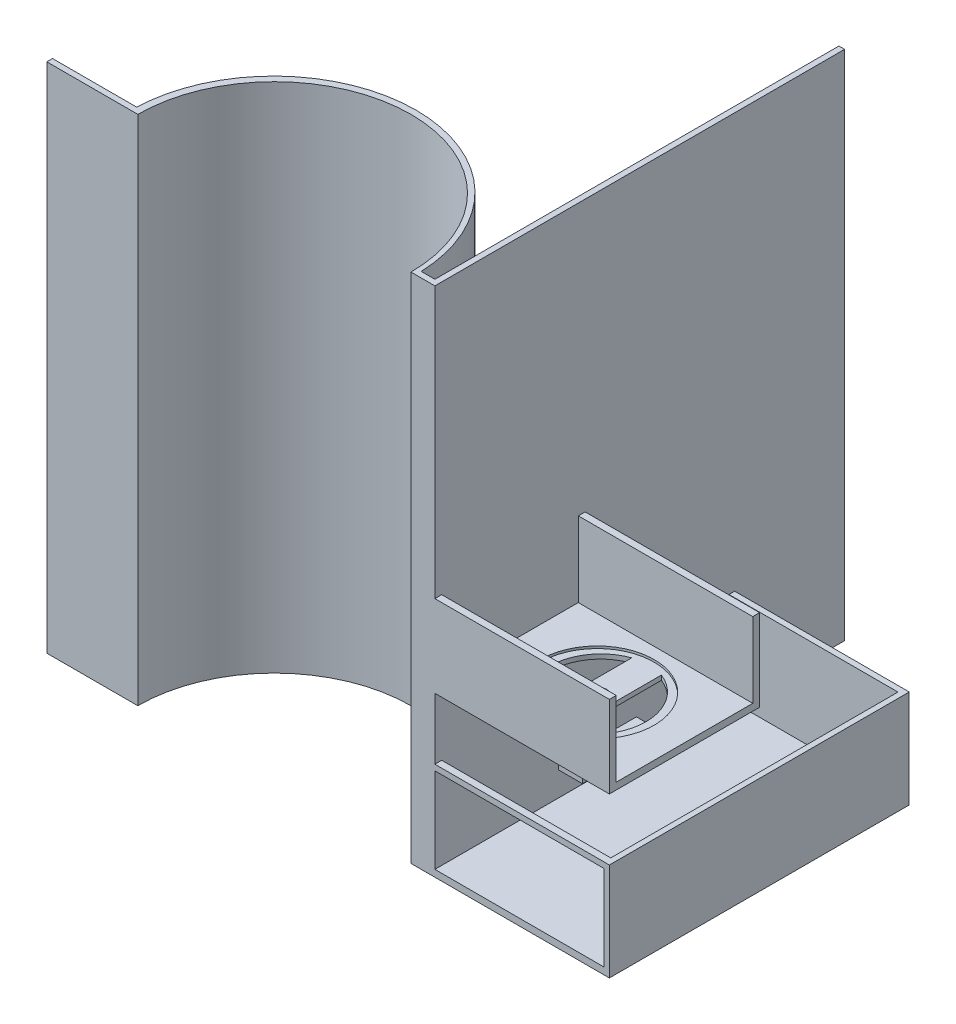
SolidWorks part; units mm, degrees
ref_plane "前视基准面" through (0, 0, 0) normal (0, 0, 1) x (1, 0, 0)
ref_plane "上视基准面" through (0, 0, 0) normal (0, 1, 0) x (1, 0, 0)
ref_plane "右视基准面" through (0, 0, 0) normal (1, 0, 0) x (0, 0, -1)
sketch "草图1" plane through (0, 0, 0) normal (0, 1, 0) x (1, 0, 0)
  line L0 (0, 0) -> (40, 0)
  line L4 (0, 0) -> (0, 2.5)
  line L5 (0, 2.5) -> (37, 2.5)
  line L6 (160, 0) -> (170.5, 0)
  line L10 (170.5, 0) -> (170.5, 180)
  line L11 (170.5, 180) -> (168, 180)
  line L12 (168, 180) -> (168, 2.5)
  line L13 (168, 2.5) -> (162, 2.5)
  arc A0 (40, 0) -> (160, 0) centre (100, 0) cw
  arc A1 (37, 2.5) -> (162, 2.5) centre (99.5, 0.1775) cw
  point P3 (160, 0)
  dimension "120" = 120
extrude "凸台-拉伸1" add sketch "草图1" along normal blind 225
ref_plane "基准面5" through (170.5, 0, 0) normal (1, 0, 0) x (0, 0, -1)
sketch "草图2" plane through (170.5, 0, 0) normal (1, 0, 0) x (0, 0, -1)
  line L0 (0, 225) -> (0, 0) construction
  line L1 (0, 70) -> (66, 70)
  point P0 (0, 70)
  dimension "D1" = 70
ref_plane "基准面6" through (0, 70, 0) normal (0, -1, 0) x (0, 0, -1)
sketch "草图3" plane through (0, 70, 0) normal (0, -1, 0) x (0, 0, -1)
  line L0 (66, 170.5) -> (66, 247.1559)
  line L1 (0, 170.5) -> (66, 170.5) construction
  line L2 (0, 170.5) -> (180, 170.5) construction
  line L3 (66, 247.1559) -> (0, 247.1559)
  line L4 (0, 247.1559) -> (0, 170.5)
  line L5 (0, 170.5) -> (66, 170.5)
extrude "凸台-拉伸2" add sketch "草图3" against normal blind 3
ref_plane "基准面7" through (0, 0, 0) normal (0, 0, 1) x (1, 0, 0)
ref_plane "基准面8" through (0, 0, -66) normal (0, 0, -1) x (-1, 0, 0)
sketch "草图4" plane through (0, 0, 0) normal (0, 0, 1) x (1, 0, 0)
  line L0 (247.1559, 73) -> (247.1559, 106)
  line L1 (247.1559, 106) -> (170.5, 106)
  line L2 (170.5, 225) -> (170.5, 73) construction
  line L3 (170.5, 106) -> (170.5, 73)
  line L4 (247.1559, 73) -> (170.5, 73) construction
  line L5 (170.5, 73) -> (247.1559, 73)
extrude "凸台-拉伸3" add sketch "草图4" against normal blind 3
sketch "草图5" plane through (0, 0, -66) normal (0, 0, -1) x (-1, 0, 0)
  line L0 (-247.1559, 73) -> (-247.1559, 106)
  line L1 (-247.1559, 106) -> (-170.5, 106)
  line L2 (-170.5, 99) -> (-170.5, -99) construction
  line L3 (-247.1559, 106) -> (-170.5, 106) construction
  line L4 (-170.5, 106) -> (-170.5, 73)
  line L5 (-170.5, 73) -> (-247.1559, 73) construction
  line L6 (-170.5, 73) -> (-247.1559, 73)
extrude "凸台-拉伸4" add sketch "草图5" against normal blind 3
ref_plane "基准面9" through (0, 73, 0) normal (0, 1, 0) x (1, 0, 0)
sketch "草图7" plane through (0, 73, 0) normal (0, 1, 0) x (1, 0, 0)
  circle A0 centre (208.8279, 33) radius 25
extrude "切除-拉伸1" cut sketch "草图7" against normal blind 1
sketch "草图8" plane through (0, 73, 0) normal (0, 1, 0) x (1, 0, 0)
  circle A0 centre (208.8279, 33) radius 4.2
extrude "切除-拉伸2" cut sketch "草图8" against normal blind 3
sketch "草图9" plane through (0, 73, 0) normal (0, 1, 0) x (1, 0, 0)
  line L0 (208.8279, 37.2) -> (208.8279, 58)
  line L1 (202.2764, 38.6038) -> (202.2764, 54.7108)
  line L2 (215.3312, 38.6038) -> (215.3312, 54.7108)
  line L3 (202.2764, 26.2458) -> (202.2764, 12.3605)
  line L4 (215.3312, 26.2458) -> (215.3312, 12.3605)
  line L5 (202.2764, 38.6038) -> (202.2764, 26.2458)
  line L6 (215.3312, 38.6038) -> (215.3312, 26.2458)
  circle A0 centre (208.8279, 33) radius 4.2 construction
  circle A1 centre (208.8279, 33) radius 25 construction
  arc A2 (202.2764, 54.7108) -> (202.2764, 12.3605) centre (209.8417, 33.5356) ccw
  arc A3 (215.3312, 54.7108) -> (215.3312, 12.3605) centre (206.9551, 33.5356) cw
extrude "切除-拉伸3" cut sketch "草图9" against normal blind 3 contours L1 A2 L3 L5 | A3 L2 L6 L4
sketch "草图10" plane through (0, 70, 0) normal (0, -1, 0) x (0, 0, -1)
  line L0 (27.1813, 214.3183) -> (27.1813, 203.7571)
  line L1 (27.1813, 203.7571) -> (21.0139, 203.7571)
  line L2 (21.0139, 203.7571) -> (21.0139, 214.3183)
  line L3 (21.0139, 214.3183) -> (27.1813, 214.3183)
extrude "凸台-拉伸5" add sketch "草图10" along normal blind 20
ref_plane "基准面10" through (0, 50, 0) normal (0, -1, 0) x (-1, 0, 0)
sketch "草图11" plane through (0, 50, 0) normal (0, -1, 0) x (-1, 0, 0)
  line L0 (-214.3183, 21.0139) -> (-214.3183, 55.2756)
  line L1 (-214.3183, 55.2756) -> (-203.7571, 55.2756)
  line L2 (-203.7571, 55.2756) -> (-203.7571, 21.0139)
  line L3 (-203.7571, 21.0139) -> (-203.7571, 27.1813) construction
  line L4 (-214.3183, 21.0139) -> (-203.7571, 21.0139) construction
  line L5 (-203.7571, 21.0139) -> (-214.3183, 21.0139)
extrude "凸台-拉伸6" add sketch "草图11" along normal blind 3
sketch "草图12" plane through (0, 0, 0) normal (0, 1, 0) x (1, 0, 0)
  line L0 (170.5, 0) -> (247.1559, 0)
  line L1 (-47.9357, 0) -> (47.9357, 0) construction
  line L2 (247.1559, 3) -> (247.1559, 0) construction
  line L3 (170.5, 0) -> (170.5, 131.6854)
  line L4 (170.5, -99) -> (170.5, 99) construction
  line L5 (170.5, 131.6854) -> (247.2052, 131.6854)
  line L6 (247.2052, 131.6854) -> (247.1559, 0)
extrude "凸台-拉伸7" add sketch "草图12" along normal blind 3
sketch "草图13" plane through (0, 0, 0) normal (0, 1, 0) x (1, 0, 0)
  line L0 (247.1559, 0) -> (247.2052, 131.6854)
  line L1 (-47.9357, 0) -> (47.9357, 0) construction
  line L2 (247.1559, 3) -> (247.1559, 0) construction
  line L3 (247.2052, 131.6854) -> (170.5, 131.6854)
  line L4 (170.5, -99) -> (170.5, 99) construction
  line L5 (247.2052, 131.6854) -> (170.5, 131.6854) construction
  line L6 (170.5, 131.6854) -> (170.5, 129.1854)
  line L7 (170.5, 129.1854) -> (244.7637, 129.1854)
  line L8 (244.7637, 129.1854) -> (244.7637, 0)
  line L9 (244.7637, 0) -> (247.1559, 0)
extrude "凸台-拉伸8" add sketch "草图13" along normal blind 43
sketch "草图15" plane through (0, 0, 0) normal (0, 0, 1) x (1, 0, 0)
  line L0 (247.1559, 43) -> (170.5, 43)
  line L1 (170.5, -99) -> (170.5, 99) construction
  line L2 (170.5, 43) -> (244.7637, 43) construction
  line L3 (170.5, 43) -> (170.5, 40.5)
  line L4 (170.5, 70) -> (170.5, 3) construction
  line L5 (170.5, 40.5) -> (247.1559, 40.5)
  line L6 (247.1559, 43) -> (247.1559, 0) construction
  line L7 (247.1559, 40.5) -> (247.1559, 43)
extrude "凸台-拉伸9" add sketch "草图15" against normal blind 3
